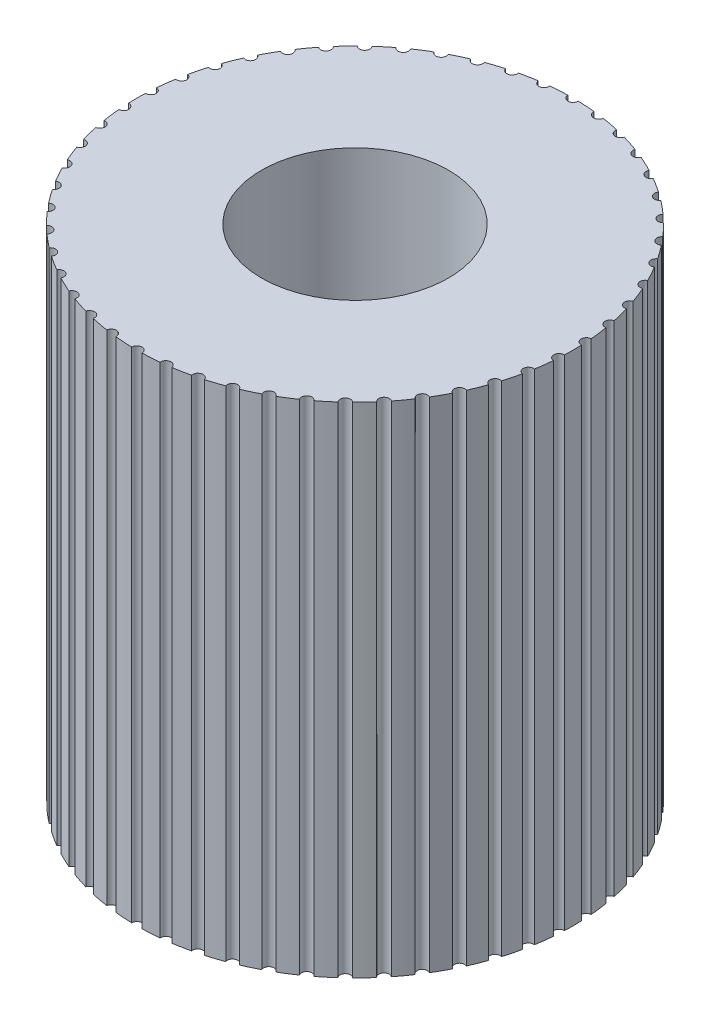
SolidWorks part; units mm, degrees
material "1060 Alloy"
ref_plane "Front Plane" through (0, 0, 0) normal (0, 0, 1) x (1, 0, 0)
ref_plane "Top Plane" through (0, 0, 0) normal (0, 1, 0) x (1, 0, 0)
ref_plane "Right Plane" through (0, 0, 0) normal (1, 0, 0) x (0, 0, -1)
sketch "Sketch1" plane through (0, 0, 0) normal (0, 1, 0) x (1, 0, 0)
  circle A0 centre (0, 0) radius 2.25
  circle A1 centre (0, 0) radius 5.25
  dimension "D1" = 4.5
  dimension "D2" = 10.5
extrude "Main Body" add sketch "Sketch1" along normal blind 12
sketch "Sketch3" plane through (0, 12, 0) normal (0, 1, 0) x (1, 0, 0)
  circle A0 centre (0, 5.25) radius 0.125
  circle A1 centre (0, 0) radius 5.25 construction
  circle A2 centre (0.658, 5.2086) radius 0.125
  circle A3 centre (1.3056, 5.0851) radius 0.125
  circle A4 centre (1.9327, 4.8813) radius 0.125
  circle A5 centre (2.5292, 4.6006) radius 0.125
  circle A6 centre (3.0859, 4.2473) radius 0.125
  circle A7 centre (3.5939, 3.8271) radius 0.125
  circle A8 centre (4.0452, 3.3465) radius 0.125
  circle A9 centre (4.4327, 2.8131) radius 0.125
  circle A10 centre (4.7503, 2.2353) radius 0.125
  circle A11 centre (4.993, 1.6223) radius 0.125
  circle A12 centre (5.157, 0.9838) radius 0.125
  circle A13 centre (5.2396, 0.3297) radius 0.125
  circle A14 centre (5.2396, -0.3297) radius 0.125
  circle A15 centre (5.157, -0.9838) radius 0.125
  circle A16 centre (4.993, -1.6223) radius 0.125
  circle A17 centre (4.7503, -2.2353) radius 0.125
  circle A18 centre (4.4327, -2.8131) radius 0.125
  circle A19 centre (4.0452, -3.3465) radius 0.125
  circle A20 centre (3.5939, -3.8271) radius 0.125
  circle A21 centre (3.0859, -4.2473) radius 0.125
  circle A22 centre (2.5292, -4.6006) radius 0.125
  circle A23 centre (1.9327, -4.8813) radius 0.125
  circle A24 centre (1.3056, -5.0851) radius 0.125
  circle A25 centre (0.658, -5.2086) radius 0.125
  circle A26 centre (0, -5.25) radius 0.125
  circle A27 centre (-0.658, -5.2086) radius 0.125
  circle A28 centre (-1.3056, -5.0851) radius 0.125
  circle A29 centre (-1.9327, -4.8813) radius 0.125
  circle A30 centre (-2.5292, -4.6006) radius 0.125
  circle A31 centre (-3.0859, -4.2473) radius 0.125
  circle A32 centre (-3.5939, -3.8271) radius 0.125
  circle A33 centre (-4.0452, -3.3465) radius 0.125
  circle A34 centre (-4.4327, -2.8131) radius 0.125
  circle A35 centre (-4.7503, -2.2353) radius 0.125
  circle A36 centre (-4.993, -1.6223) radius 0.125
  circle A37 centre (-5.157, -0.9838) radius 0.125
  circle A38 centre (-5.2396, -0.3297) radius 0.125
  circle A39 centre (-5.2396, 0.3297) radius 0.125
  circle A40 centre (-5.157, 0.9838) radius 0.125
  circle A41 centre (-4.993, 1.6223) radius 0.125
  circle A42 centre (-4.7503, 2.2353) radius 0.125
  circle A43 centre (-4.4327, 2.8131) radius 0.125
  circle A44 centre (-4.0452, 3.3465) radius 0.125
  circle A45 centre (-3.5939, 3.8271) radius 0.125
  circle A46 centre (-3.0859, 4.2473) radius 0.125
  circle A47 centre (-2.5292, 4.6006) radius 0.125
  circle A48 centre (-1.9327, 4.8813) radius 0.125
  circle A49 centre (-1.3056, 5.0851) radius 0.125
  circle A50 centre (-0.658, 5.2086) radius 0.125
  point P105 (0, 0)
  dimension "D1" = 0.25
  dimension "D3" = 5.25
  dimension "D4" = 5.25
  dimension "D2" = 50
extrude "Cut" cut sketch "Sketch3" against normal through all both and the other way through all
